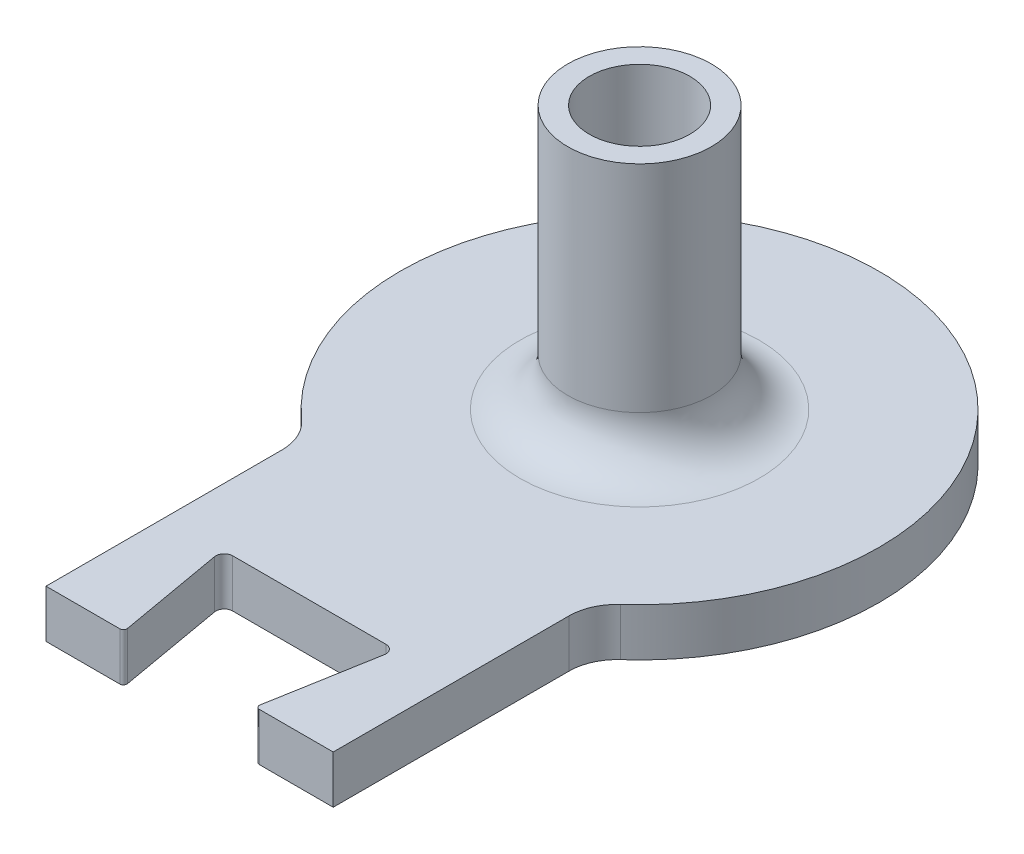
SolidWorks part; units mm, degrees
ref_plane "Front Plane" through (0, 0, 0) normal (0, 0, 1) x (1, 0, 0)
ref_plane "Top Plane" through (0, 0, 0) normal (0, 1, 0) x (1, 0, 0)
ref_plane "Right Plane" through (0, 0, 0) normal (1, 0, 0) x (0, 0, -1)
sketch "Sketch1" plane through (0, 0, 0) normal (0, 1, 0) x (1, 0, 0)
  line L0 (-6, 6) -> (-6, -13.2915)
  line L1 (-6, -19) -> (-2.7023, -19)
  line L2 (6, -19) -> (6, -13.2915)
  line L3 (6, 6) -> (-6, 6)
  line L4 (-6, -13.2915) -> (-6, -19)
  line L5 (6, -13.2915) -> (6, 6)
  line L6 (0, -19) -> (0, 0) construction
  line L7 (-2.6007, -19) -> (-3.5, -13.9) construction
  line L8 (-3.5, -13.9) -> (0, -13.9) construction
  line L9 (-2.7023, -19) -> (-3.6192, -13.8)
  line L10 (-3.6192, -13.8) -> (0, -13.8)
  line L11 (-2.6992, -19.0174) -> (-3.6192, -13.8) construction
  line L12 (2.7023, -19) -> (6, -19)
  line L13 (3.6192, -13.8) -> (0, -13.8)
  line L14 (2.7023, -19) -> (3.6192, -13.8)
  circle A0 centre (0, 0) radius 0.25
  dimension "D1" = 0.5
  dimension "D5" = 6
  dimension "D7" = 80
  dimension "D2" = 25
  dimension "D3" = 6
  dimension "D4" = 12
  dimension "D8" = 3.5
  dimension "D9" = 5.1
  dimension "D10" = 0.1
extrude "Boss-Extrude1" add sketch "Sketch1" along normal blind 2
sketch "Sketch2" plane through (0, 0, 0) normal (0, 1, 0) x (1, 0, 0)
  circle A0 centre (0, 0) radius 10
  circle A1 centre (0, 0) radius 3
  dimension "D1" = 20
extrude "Boss-Extrude2" add sketch "Sketch2" along normal blind 2
sketch "Sketch3" plane through (0, 0, 0) normal (0, -1, 0) x (1, 0, 0)
  line L0 (-3, 0) -> (-3, 4)
  line L1 (3, 0) -> (3, 4)
  arc A0 (-3, 0) -> (3, 0) centre (0, 0) ccw
  arc A1 (-3, 4) -> (3, 4) centre (0, 0) ccw
extrude "Boss-Extrude3" [suppressed] add sketch "Sketch3" along normal blind 4
fillet "Fillet1" [suppressed] radius 0.5
fillet "Fillet2" [suppressed] radius 1
sketch "Sketch4" plane through (0, 2, 0) normal (0, 1, 0) x (1, 0, 0)
  line L0 (-6, -8) -> (-6, -19) construction
  line L1 (-6, -18.8) -> (6, -18.8)
  line L2 (-6, -18.8) -> (-6, -19)
  line L3 (-6, -19) -> (6, -19)
  line L4 (6, -18.8) -> (6, -19)
  dimension "D1" = 0.2
extrude "Cut-Extrude1" cut sketch "Sketch4" against normal blind 4
fillet "Fillet3" radius 0.35 2 edges at (3.6192, 1, 13.8) (-3.6192, 1, 13.8)
fillet "Fillet4" radius 0.15 2 edges at (2.7375, 1, 18.8) (-2.7375, 1, 18.8)
sketch "Sketch5" plane through (0, 0, 0) normal (0, 1, 0) x (1, 0, 0)
  circle A1 centre (0, 0) radius 3
  circle A2 centre (0, 0) radius 2.1
  dimension "D1" = 4.2
  dimension "D2" = 6
extrude "Boss-Extrude4" add sketch "Sketch5" along normal blind 13
fillet "Fillet5" radius 2 1 edges at (0, 2, 3)
fillet "Fillet6" radius 2 2 edges at (-6, 1, 8) (6, 1, 8)
